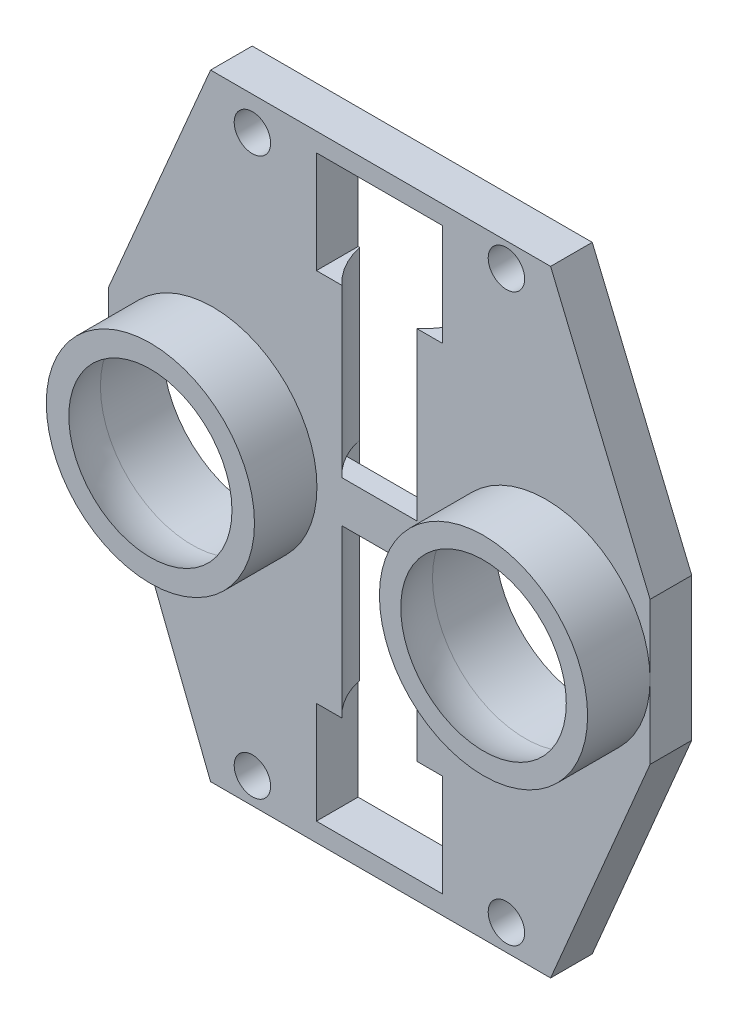
SolidWorks part; units mm, degrees
ref_plane "Alzado" through (0, 0, 0) normal (0, 0, 1) x (1, 0, 0)
ref_plane "Planta" through (0, 0, 0) normal (0, 1, 0) x (1, 0, 0)
ref_plane "Vista lateral" through (0, 0, 0) normal (1, 0, 0) x (0, 0, -1)
sketch "Croquis1" plane through (0, 0, 0) normal (0, 0, 1) x (1, 0, 0)
  line L1 (0, 0) -> (22, 0)
  line L2 (0, 0) -> (0, 55.2)
  line L3 (0, 55.2) -> (22, 55.2)
  line L4 (22, 0) -> (22, 55.2)
  dimension "D1" = 55.2
  dimension "D2" = 22
extrude "Saliente-Extruir1" add sketch "Croquis1" along normal blind 4
sketch "Croquis2" plane through (0, 55.2, 0) normal (0, 1, 0) x (1, 0, 0)
  line L0 (22, 0) -> (0, 0) construction
  line L1 (4.95, 0) -> (17.05, 0)
  line L2 (4.95, 0) -> (4.95, -4)
  line L3 (4.95, -4) -> (17.05, -4)
  line L4 (17.05, 0) -> (17.05, -4)
  line L5 (22, -4) -> (0, -4) construction
  line L6 (0, -4) -> (0, 0) construction
  dimension "D1" = 12.1
  dimension "D2" = 4.95
extrude "Cortar-Extruir1" cut sketch "Croquis2" against normal blind 9.6
sketch "Croquis3" plane through (0, 0, 0) normal (0, -1, 0) x (1, 0, 0)
  line L0 (0, 4) -> (22, 4) construction
  line L1 (4.95, 4) -> (17.05, 4)
  line L2 (4.95, 4) -> (4.95, 0)
  line L3 (4.95, 0) -> (17.05, 0)
  line L4 (17.05, 4) -> (17.05, 0)
  line L5 (0, 0) -> (22, 0) construction
  line L6 (0, 4) -> (0, 0) construction
  line L7 (22, 4) -> (22, 0) construction
  dimension "D1" = 4.95
  dimension "D2" = 4.95
extrude "Cortar-Extruir2" cut sketch "Croquis3" against normal blind 9.6
sketch "Croquis5" plane through (0, 9.6, 0) normal (0, -1, 0) x (1, 0, 0)
  line L0 (7.4, 4) -> (14.6, 4)
  line L1 (17.05, 4) -> (4.95, 4) construction
  line L2 (4.95, -1.5) -> (17.05, -1.5)
  arc A2 (7.4, 4) -> (4.95, -1.5) centre (12.4499, -1.5452) ccw
  arc A3 (17.05, -1.5) -> (14.6, 4) centre (9.5501, -1.5452) ccw
  dimension "D1" = 7.2
  dimension "D2" = 2.45
extrude "Cortar-Extruir3" cut sketch "Croquis5" against normal blind 16
sketch "Croquis7" plane through (0, 45.6, 0) normal (0, 1, 0) x (1, 0, 0)
  line L5 (4.95, -4) -> (17.05, -4) construction
  line L11 (4.95, 1.5) -> (17.05, 1.5)
  line L12 (7.4, -4) -> (14.6, -4)
  arc A3 (4.95, 1.5) -> (7.4, -4) centre (12.4499, 1.5452) ccw
  arc A4 (14.6, -4) -> (17.05, 1.5) centre (9.5501, 1.5452) ccw
extrude "Cortar-Extruir4" cut sketch "Croquis7" against normal blind 16
sketch "Croquis9" plane through (0, 0, 0) normal (0, 0, -1) x (-1, 0, 0)
  line L1 (-16.8892, 29.6) -> (-5.1108, 29.6)
  line L2 (-16.8892, 29.6) -> (-16.8892, 25.6)
  line L3 (-16.8892, 25.6) -> (-5.1108, 25.6)
  line L4 (-5.1108, 29.6) -> (-5.1108, 25.6)
extrude "Cortar-Extruir5" cut sketch "Croquis9" against normal blind 2
sketch "Croquis10" plane through (0, 0, 2) normal (0, 0, -1) x (-1, 0, 0)
  line L1 (-16.8892, 29.6) -> (-16.8892, 25.6) construction
  line L4 (-13.4992, 26) -> (-8.4992, 26)
  line L6 (-13.4992, 29) -> (-8.4992, 29)
  line L10 (-13.4992, 26) -> (-13.4992, 29)
  line L11 (-8.4992, 29) -> (-8.4992, 26)
  dimension "D1" = 5
  dimension "D2" = 3.39
sketch "Croquis11" plane through (0, 55.2, 0) normal (0, 1, 0) x (1, 0, 0)
  line L0 (0, -4) -> (4.95, -4) construction
  line L1 (4.95, -4) -> (4.95, 0) construction
  line L2 (4.95, 0) -> (0, 0) construction
  line L3 (0, 0) -> (0, -4) construction
  line L4 (22, 0) -> (17.05, 0) construction
  line L5 (17.05, 0) -> (17.05, -4) construction
  line L6 (17.05, -4) -> (22, -4) construction
  line L7 (22, -4) -> (22, 0) construction
  line L8 (0, -4) -> (4.95, -4)
  line L9 (4.95, -4) -> (4.95, 0)
  line L10 (4.95, 0) -> (0, 0)
  line L11 (0, 0) -> (0, -4)
  line L12 (22, 0) -> (17.05, 0)
  line L13 (17.05, 0) -> (17.05, -4)
  line L14 (17.05, -4) -> (22, -4)
  line L15 (22, -4) -> (22, 0)
extrude "Saliente-Extruir3" add sketch "Croquis11" along normal blind 2
sketch "Croquis12" plane through (4.95, 0, 0) normal (1, 0, 0) x (0, 0, -1)
  line L0 (-4, 57.2) -> (0, 57.2)
  line L1 (0, 57.2) -> (0, 55.4)
  line L2 (0, 45.6) -> (0, 57.2) construction
  line L3 (0, 55.4) -> (-4, 55.4)
  line L4 (-4, 45.6) -> (-4, 57.2) construction
  line L5 (-4, 55.4) -> (-4, 57.2)
extrude "Saliente-Extruir4" add sketch "Croquis12" along normal blind 12.1
sketch "Croquis13" plane through (0, 0, 0) normal (0, -1, 0) x (1, 0, 0)
  line L0 (22, 4) -> (17.05, 4) construction
  line L1 (17.05, 4) -> (17.05, 0) construction
  line L2 (17.05, 0) -> (22, 0) construction
  line L3 (22, 0) -> (22, 4) construction
  line L4 (0, 0) -> (4.95, 0) construction
  line L5 (4.95, 0) -> (4.95, 4) construction
  line L6 (4.95, 4) -> (0, 4) construction
  line L7 (0, 4) -> (0, 0) construction
  line L8 (22, 4) -> (17.05, 4)
  line L9 (17.05, 4) -> (17.05, 0)
  line L10 (17.05, 0) -> (22, 0)
  line L11 (22, 0) -> (22, 4)
  line L12 (0, 0) -> (4.95, 0)
  line L13 (4.95, 0) -> (4.95, 4)
  line L14 (4.95, 4) -> (0, 4)
  line L15 (0, 4) -> (0, 0)
extrude "Saliente-Extruir5" add sketch "Croquis13" along normal blind 2
sketch "Croquis14" plane through (4.95, 0, 0) normal (1, 0, 0) x (0, 0, -1)
  line L0 (-4, 9.6) -> (-4, -2) construction
  line L1 (0, -2) -> (-4, -2)
  line L2 (0, -2) -> (0, -0.2)
  line L3 (0, -0.2) -> (-4, -0.2)
  line L4 (-4, -2) -> (-4, -0.2)
extrude "Saliente-Extruir6" add sketch "Croquis14" along normal blind 12.1
sketch "Croquis17" plane through (0, 0, 0) normal (-1, 0, 0) x (0, 0, 1)
  line L4 (0, 57.2) -> (0, -2)
  line L5 (0, -2) -> (4, -2)
  line L6 (4, -2) -> (4, 57.2)
  line L7 (4, 57.2) -> (0, 57.2)
  line L8 (0, 57.2) -> (0, -2)
  line L9 (0, -2) -> (4, -2)
  line L10 (4, -2) -> (4, 57.2)
  line L11 (4, 57.2) -> (0, 57.2)
  dimension "D1" = 0
extrude "Saliente-Extruir8" add sketch "Croquis17" along normal blind 15 contours L8 L9 L10 L11
sketch "Croquis18" plane through (22, 0, 0) normal (1, 0, 0) x (0, 0, -1)
  line L4 (0, -2) -> (0, 57.2)
  line L5 (0, 57.2) -> (-4, 57.2)
  line L6 (-4, 57.2) -> (-4, -2)
  line L7 (-4, -2) -> (0, -2)
  line L8 (0, -2) -> (0, 57.2)
  line L9 (0, 57.2) -> (-4, 57.2)
  line L10 (-4, 57.2) -> (-4, -2)
  line L11 (-4, -2) -> (0, -2)
  dimension "D1" = 0
extrude "Saliente-Extruir9" add sketch "Croquis18" along normal blind 15
sketch "Croquis19" plane through (0, 0, 0) normal (0, 0, -1) x (-1, 0, 0)
  line L0 (15, -2) -> (-37, -2) construction
  line L5 (15, 57.2) -> (15, -2) construction
  circle A0 centre (-23.2, 54.9) radius 1.75
  circle A1 centre (1.2, 54) radius 1.75
  circle A2 centre (1.2, 0.5) radius 1.75
  circle A3 centre (-23.2, 0.5) radius 1.75
  dimension "D1" = 3.5
  dimension "D2" = 3.5
  dimension "D3" = 3.5
  dimension "D4" = 3.5
  dimension "D5" = 2.5
  dimension "D6" = 2.5
  dimension "D7" = 54.4
  dimension "D8" = 13.8
  dimension "D9" = 24.4
  dimension "D10" = 24.4
  dimension "D12" = 13.8
extrude "Cortar-Extruir6" cut sketch "Croquis19" against normal blind 11.5
sketch "Croquis20" plane through (0, 0, 0) normal (0, 0, -1) x (-1, 0, 0)
  line L0 (15, 27.6) -> (-38.1967, 27.6) construction
  line L1 (15, 57.2) -> (15, -2) construction
  line L2 (-37, -2) -> (-37, 57.2) construction
  circle A0 centre (5, 27.6) radius 8.8
  circle A1 centre (-27, 27.6) radius 8.901
  dimension "D1" = 10
  dimension "D2" = 10
extrude "Cortar-Extruir7" cut sketch "Croquis20" against normal blind 4
sketch "Croquis22" plane through (0, 0, 4) normal (0, 0, 1) x (1, 0, 0)
  line L0 (27, 36.501) -> (27, 18.699) construction
  circle A0 centre (-5, 27.6) radius 10
  circle A1 centre (27, 27.6) radius 8.901 construction
  circle A2 centre (27, 27.6) radius 10
extrude "Saliente-Extruir10" add sketch "Croquis22" along normal blind 6
sketch "Croquis25" plane through (0, 0, 0) normal (0, 0, -1) x (-1, 0, 0)
  line L0 (-37, 27.6) -> (15, 27.6) construction
  line L1 (-27.4443, 57.2) -> (-37, 34.2758)
  line L2 (-37, 57.2) -> (15, 57.2) construction
  line L3 (-37, -2) -> (-37, 57.2) construction
  line L4 (-37, 34.2758) -> (-37, 57.2)
  line L5 (-37, 57.2) -> (-27.4443, 57.2)
  line L6 (5.218, 57.2) -> (15, 34.2758)
  line L7 (15, 57.2) -> (15, -2) construction
  line L8 (15, 34.2758) -> (15, 57.2)
  line L9 (15, 57.2) -> (5.218, 57.2)
  line L10 (-37, 20.5471) -> (-27.4443, -2)
  line L11 (15, -2) -> (-37, -2) construction
  line L12 (-27.4443, -2) -> (-37, -2)
  line L13 (-37, -2) -> (-37, 20.5471)
  line L14 (5.218, -2) -> (15, 22.81)
  line L15 (15, 22.81) -> (15, -2)
  line L16 (15, -2) -> (5.218, -2)
extrude "Cortar-Extruir8" cut sketch "Croquis25" against normal blind 10
sketch "Croquis26" plane through (0, 0, 4) normal (0, 0, -1) x (-1, 0, 0)
  circle A0 centre (-27, 27.6) radius 8.901 construction
  circle A1 centre (5, 27.6) radius 8.8 construction
  circle A2 centre (-27, 27.6) radius 8.901
  circle A3 centre (5, 27.6) radius 8.8
extrude "Cortar-Extruir9" cut sketch "Croquis26" against normal blind 2
sketch "Croquis27" plane through (0, 0, 6) normal (0, 0, -1) x (-1, 0, 0)
  line L0 (5, 36.4) -> (5, 18.8)
  circle A1 centre (5, 27.6) radius 8.8
  arc A2 (5, 18.8) -> (5, 36.4) centre (5, 27.6) ccw
  dimension "D1" = 0
revolve "Cortar-Revolución1" cut sketch "Croquis27" angle 360 about L0
sketch "Croquis28" plane through (0, 0, 6) normal (0, 0, -1) x (-1, 0, 0)
  line L0 (-27, 36.501) -> (-27, 18.699)
  circle A1 centre (-27, 27.6) radius 8.901
  arc A2 (-27, 36.501) -> (-27, 18.699) centre (-27, 27.6) ccw
  dimension "D1" = 0
revolve "Cortar-Revolución2" cut sketch "Croquis28" angle 360 about L0
